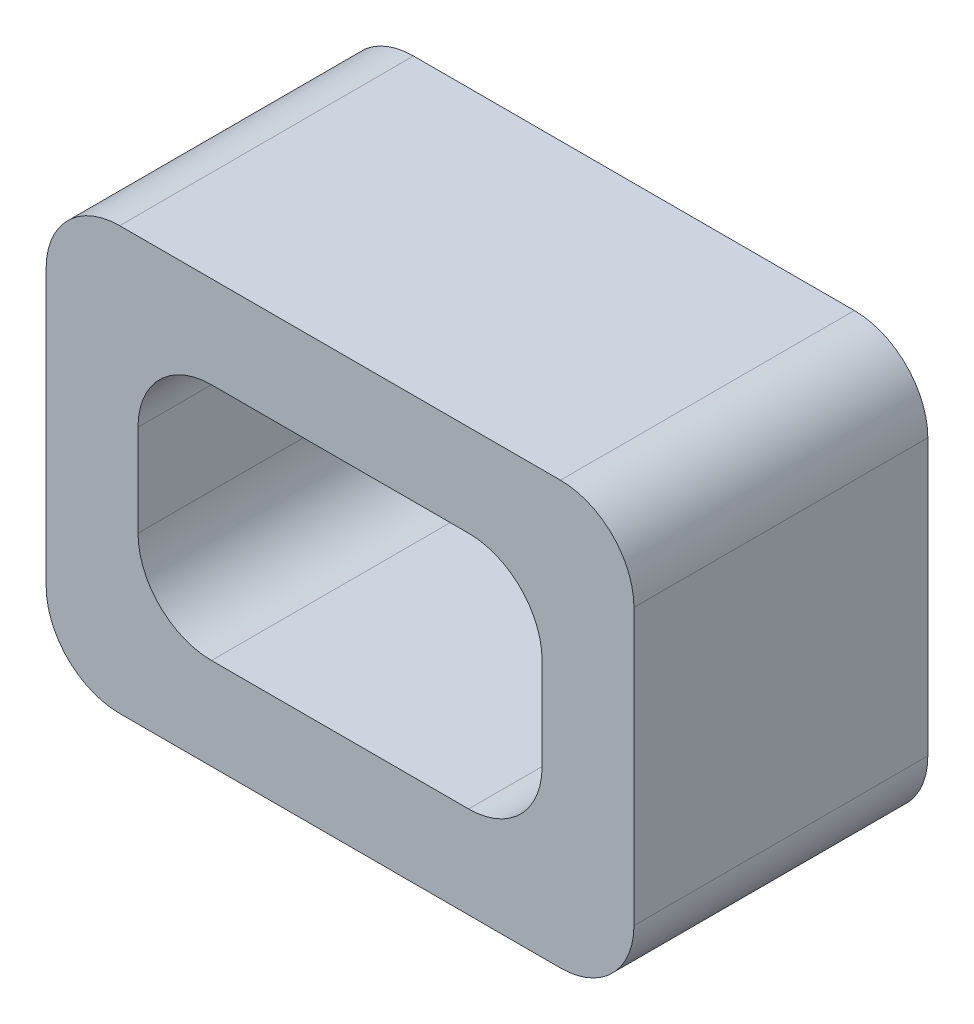
SolidWorks part; units mm, degrees
ref_plane "Front Plane" through (0, 0, 0) normal (0, 0, 1) x (1, 0, 0)
ref_plane "Top Plane" through (0, 0, 0) normal (0, 1, 0) x (1, 0, 0)
ref_plane "Right Plane" through (0, 0, 0) normal (1, 0, 0) x (0, 0, -1)
sketch "Sketch1" plane through (0, 0, 0) normal (0, 0, 1) x (1, 0, 0)
  line L1 (0, 0) -> (-1.6, 0)
  line L2 (0, 0) -> (0, 1.15)
  line L3 (0, 1.15) -> (-1.6, 1.15)
  line L4 (-1.6, 0) -> (-1.6, 1.15)
  dimension "D1" = 1.6
  dimension "D2" = 1.15
extrude "Boss-Extrude1" add sketch "Sketch1" along normal blind 0.8
fillet "Fillet1" radius 0.2 4 edges at (-1.6, 0, 0.4) (-1.6, 1.15, 0.4) (0, 0, 0.4) (0, 1.15, 0.4)
sketch "Sketch2" plane through (0, 0, 0.8) normal (0, 0, 1) x (1, 0, 0)
  line L36 (-1.35, 0.25) -> (-0.25, 0.25)
  line L37 (-0.25, 0.25) -> (-0.25, 0.9)
  line L38 (-0.25, 0.9) -> (-1.35, 0.9)
  line L39 (-1.35, 0.9) -> (-1.35, 0.25)
  line L40 (-1.35, 0.25) -> (-0.25, 0.25)
  line L41 (-0.25, 0.25) -> (-0.25, 0.9)
  line L42 (-0.25, 0.9) -> (-1.35, 0.9)
  line L43 (-1.35, 0.9) -> (-1.35, 0.25)
  dimension "D2" = 0.25
extrude "Cut-Extrude1" cut sketch "Sketch2" against normal blind 0.8
fillet "Fillet2" radius 0.2 4 edges at (-0.25, 0.9, 0.4) (-1.35, 0.9, 0.4) (-1.35, 0.25, 0.4) (-0.25, 0.25, 0.4)
